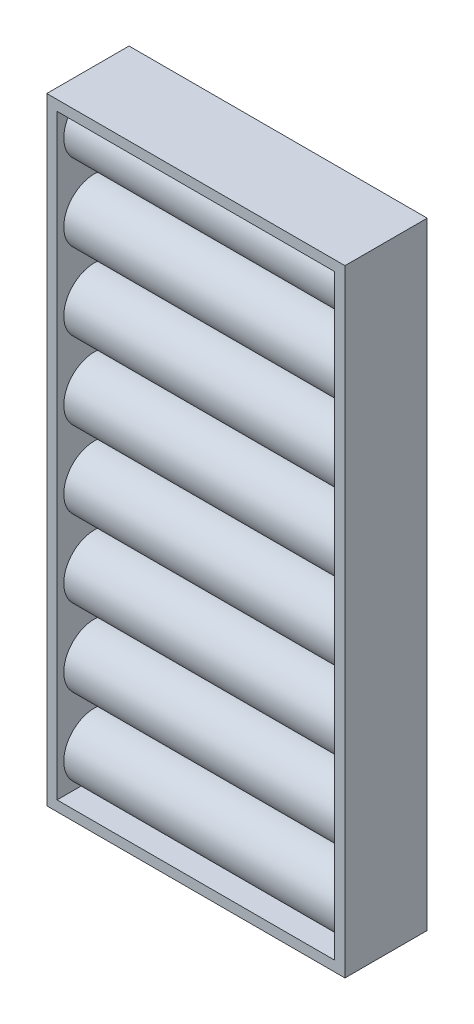
SolidWorks part; units mm, degrees
ref_plane "Ön Düzlem" through (0, 0, 0) normal (0, 0, 1) x (1, 0, 0)
ref_plane "Üst Düzlem" through (0, 0, 0) normal (0, 1, 0) x (1, 0, 0)
ref_plane "Sağ Düzlem" through (0, 0, 0) normal (1, 0, 0) x (0, 0, -1)
sketch "Çizim1" plane through (0, 0, 0) normal (0, 0, 1) x (1, 0, 0)
  line L1 (-29, 60) -> (29, 60)
  line L2 (-29, 60) -> (-29, -60)
  line L3 (-29, -60) -> (29, -60)
  line L4 (29, 60) -> (29, -60)
  line L5 (-29, 60) -> (29, -60) construction
  line L6 (-29, -60) -> (29, 60) construction
  point P0 (0, 0)
  dimension "D1" = 58
  dimension "D2" = 120
extrude "Yükseklik-Ekstrüzyon1" add sketch "Çizim1" along normal blind 16
shell "İç Boşaltma1" thickness 2
sketch "Çizim2" plane through (-27, 0, 0) normal (1, 0, 0) x (0, 0, -1)
  circle A0 centre (-8.693, -52.1503) radius 6
  circle A1 centre (-8.693, -37.1503) radius 6
  circle A2 centre (-8.693, -22.1503) radius 6
  circle A3 centre (-8.693, -7.1503) radius 6
  circle A4 centre (-8.693, 7.8497) radius 6
  circle A5 centre (-8.693, 22.8497) radius 6
  circle A6 centre (-8.693, 37.8497) radius 6
  circle A7 centre (-8.693, 52.8497) radius 6
  point P2 (-8.693, -52.1503)
  dimension "D1" = 12
  dimension "D2" = 8
extrude "Yükseklik-Ekstrüzyon2" add sketch "Çizim2" along normal up to surface (54 mm away) separate body up to face at (27, 0, 9)
